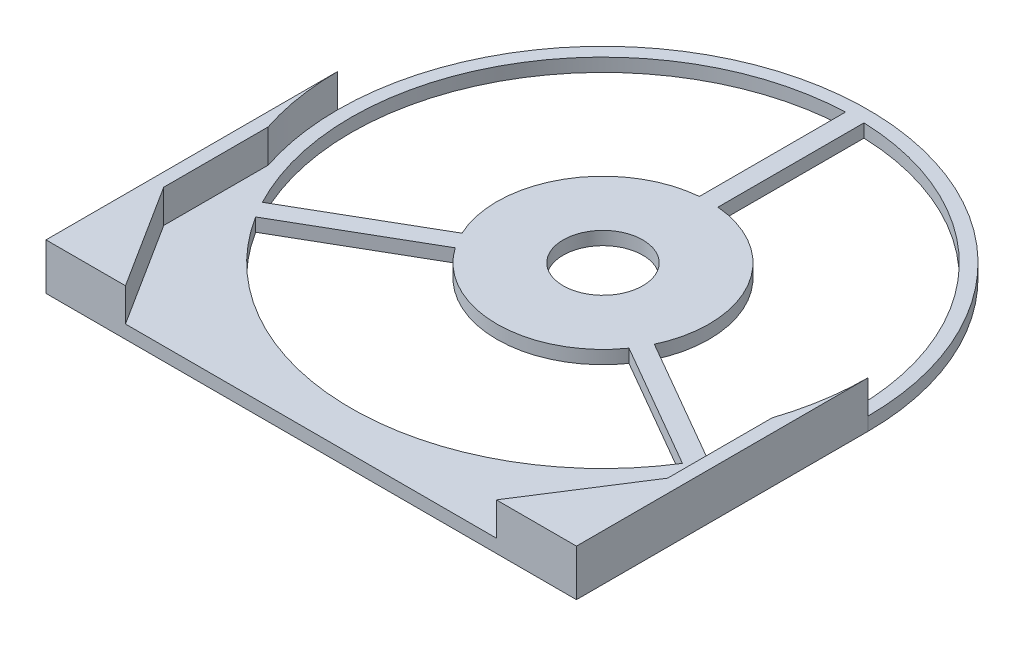
SolidWorks part; units mm, degrees
material "PP 均聚物"
ref_plane "前视基准面" through (0, 0, 0) normal (0, 0, 1) x (1, 0, 0)
ref_plane "上视基准面" through (0, 0, 0) normal (0, 1, 0) x (1, 0, 0)
ref_plane "右视基准面" through (0, 0, 0) normal (1, 0, 0) x (0, 0, -1)
sketch "草图1" plane through (0, 0, 0) normal (0, 1, 0) x (1, 0, 0)
  line L1 (-20, 0) -> (20, 0)
  line L2 (-20, 0) -> (-20, -22)
  line L3 (-20, -22) -> (20, -22)
  line L4 (20, 0) -> (20, -22)
  circle A0 centre (0, 0) radius 20
  dimension "D1" = 40
  dimension "D2" = 22
  dimension "D3" = 40
extrude "凸台-拉伸4" add sketch "草图1" along normal blind 1 contours L1 A0 | L1 A0 | A0 L2 L3 L4
sketch "草图4" plane through (0, 1, 0) normal (0, 1, 0) x (1, 0, 0)
  line L0 (-20, -22) -> (20, -22) construction
  line L1 (-20, 0) -> (20, 0)
  line L2 (-20, 0) -> (-20, -22)
  line L3 (-20, -22) -> (20, -22)
  line L4 (20, 0) -> (20, -22)
  circle A0 centre (0, 0) radius 20
  line M1 (20, -22) -> (20, 0)
  line M3 (-20, 0) -> (-20, -22)
  line M4 (-20, -22) -> (20, -22)
extrude "凸台-拉伸5" add sketch "草图4" along normal blind 2.5 contours A0 M3 M4 M1
sketch "草图5" plane through (0, 1, 0) normal (0, 1, 0) x (1, 0, 0)
  line L0 (0.35, 0.6062) -> (19.4026, -10.3938)
  line L1 (-0.7, 0) -> (0.7, 0)
  line L2 (-0.7, 0) -> (-0.7, 22)
  line L3 (-0.7, 22) -> (0.7, 22)
  line L4 (0.7, 0) -> (0.7, 22)
  line L5 (-0.35, -0.6062) -> (18.7026, -11.6062)
  line L6 (0.35, 0.6062) -> (-0.35, -0.6062)
  line L7 (19.4026, -10.3938) -> (18.7026, -11.6062)
  line L8 (0.35, -0.6062) -> (-18.7026, -11.6062)
  line L9 (-0.35, 0.6062) -> (-19.4026, -10.3938)
  line L10 (0.35, -0.6062) -> (-0.35, 0.6062)
  line L11 (-18.7026, -11.6062) -> (-19.4026, -10.3938)
  circle A0 centre (0, 0) radius 8
  circle A1 centre (0, 0) radius 19
  point P19 (0, 0)
  dimension "D1" = 16
  dimension "D2" = 38
  dimension "D3" = 1.4
  dimension "D4" = 22
  dimension "D5" = 3
extrude "切除-拉伸2" cut sketch "草图5" against normal through all contours L2 A1 L9 A0 | L0 A1 L4 A0 | L8 A1 L5 A0
sketch "草图6" plane through (0, 1, 0) normal (0, 1, 0) x (1, 0, 0)
  circle A0 centre (0, 0) radius 3
  dimension "D1" = 6
extrude "切除-拉伸3" cut sketch "草图6" against normal through all
sketch "草图7" plane through (0, 0, 22) normal (0, 0, 1) x (1, 0, 0)
  line L0 (-20, 3.5) -> (20, 3.5) construction
  line L1 (-19, 3.5) -> (19, 3.5)
  line L2 (-19, 3.5) -> (-19, 1)
  line L3 (-19, 1) -> (19, 1)
  line L4 (19, 3.5) -> (19, 1)
  line L5 (-20, 3.5) -> (-20, 0) construction
  line L6 (20, 3.5) -> (20, 0) construction
  dimension "D1" = 2.5
  dimension "D2" = 1
  dimension "D3" = 1
extrude "切除-拉伸4" cut sketch "草图7" against normal through all
sketch "草图8" plane through (0, 1, 0) normal (0, 1, 0) x (1, 0, 0)
  line L0 (19, -14.1225) -> (13.9609, -22)
  line L1 (19, -22) -> (19, -6.245) construction
  line L2 (-19, -22) -> (19, -22) construction
  line L3 (13.9609, -50) -> (13.9609, -22) construction
  line L4 (13.9609, -22) -> (19, -22)
  line L5 (19, -22) -> (19, -14.1225)
  line L6 (-19, -14.1225) -> (-14.0077, -22)
  line L7 (-19, -6.245) -> (-19, -22) construction
  line L8 (-14.0077, -22) -> (-19, -22)
  line L9 (-19, -22) -> (-19, -14.1225)
extrude "凸台-拉伸6" add sketch "草图8" along normal blind 2.5
